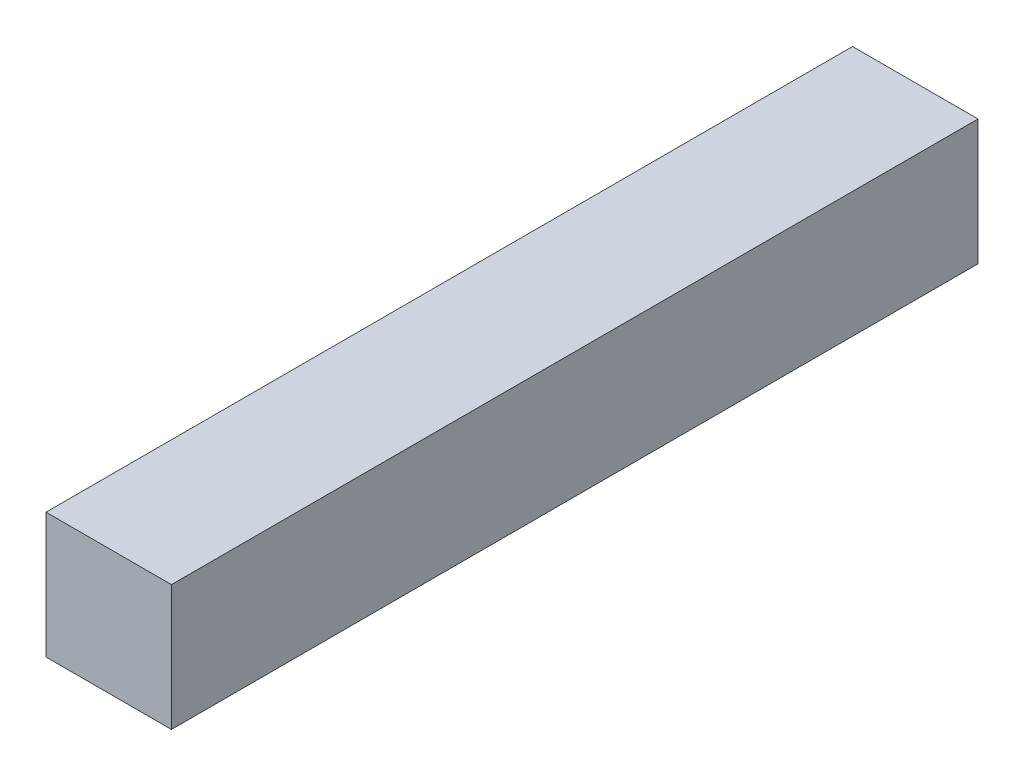
SolidWorks part; units mm, degrees
ref_plane "Front Plane" through (0, 0, 0) normal (0, 0, 1) x (1, 0, 0)
ref_plane "Top Plane" through (0, 0, 0) normal (0, 1, 0) x (1, 0, 0)
ref_plane "Right Plane" through (0, 0, 0) normal (1, 0, 0) x (0, 0, -1)
sketch "Sketch1" plane through (0, 0, 0) normal (0, 0, 1) x (1, 0, 0)
  line L1 (0, 0) -> (2.8, 0)
  line L2 (0, 0) -> (0, 2.8)
  line L3 (0, 2.8) -> (2.8, 2.8)
  line L4 (2.8, 0) -> (2.8, 2.8)
  dimension "D1" = 2.8
extrude "Boss-Extrude1" add sketch "Sketch1" along normal blind 18
